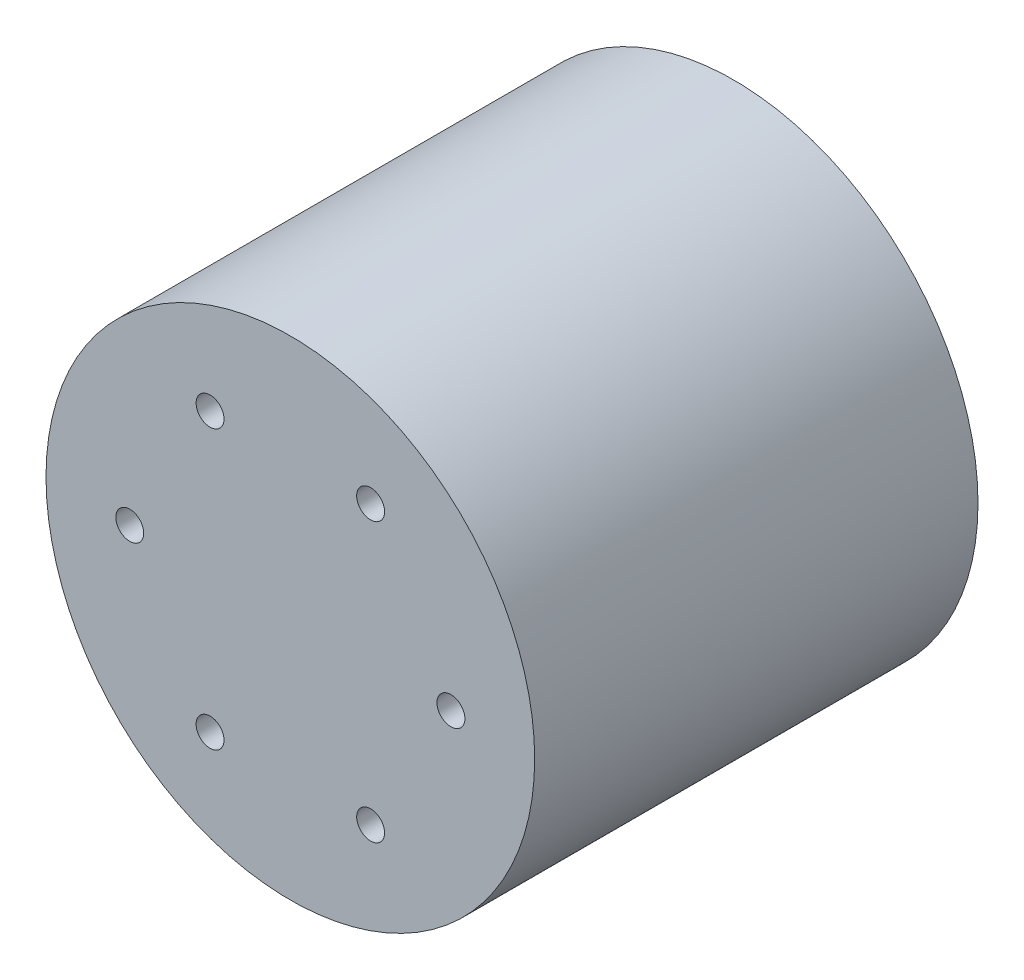
SolidWorks part; units mm, degrees
ref_plane "前视基准面" through (0, 0, 0) normal (0, 0, 1) x (1, 0, 0)
ref_plane "上视基准面" through (0, 0, 0) normal (0, 1, 0) x (1, 0, 0)
ref_plane "右视基准面" through (0, 0, 0) normal (1, 0, 0) x (0, 0, -1)
sketch "草图1" plane through (0, 0, 0) normal (0, 0, 1) x (1, 0, 0)
  circle A0 centre (0, 0) radius 35
  dimension "D1" = 70
extrude "凸台-拉伸2" add sketch "草图1" along normal blind 63.5
sketch "草图3" plane through (0, 0, 63.5) normal (0, 0, 1) x (1, 0, 0)
  circle A0 centre (0, 0) radius 23
  circle A1 centre (-23, 0) radius 2
  circle A2 centre (-11.5, 19.9186) radius 2
  circle A3 centre (11.5, 19.9186) radius 2
  circle A4 centre (23, 0) radius 2
  circle A5 centre (11.5, -19.9186) radius 2
  circle A6 centre (-11.5, -19.9186) radius 2
  point P17 (0, 0)
  dimension "D1" = 46
  dimension "D2" = 6
extrude "切除-拉伸1" cut sketch "草图3" against normal blind 20 contours A0 A2 | A0 A2 | A0 A6 | A0 A6 | A0 A5 | A0 A5 | A0 A4 | A0 A4 | A0 A3 | A0 A3 | A0 A1 | A0 A1
ref_plane "基准面4" through (0, 0, 31.75) normal (0, 0, 1) x (1, 0, 0)
mirror "镜向1" about plane through (0, 0, 31.75) normal (0, 0, 1) of "切除-拉伸1"
